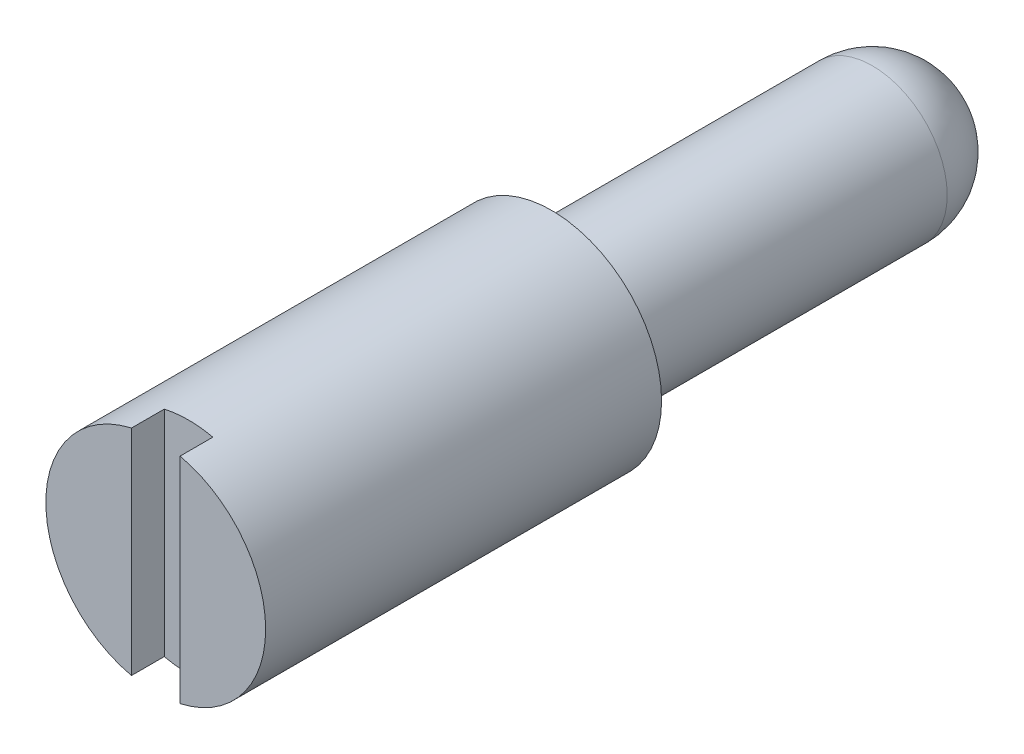
SolidWorks part; units mm, degrees
ref_plane "Front Plane" through (0, 0, 0) normal (0, 0, 1) x (1, 0, 0)
ref_plane "Top Plane" through (0, 0, 0) normal (0, 1, 0) x (1, 0, 0)
ref_plane "Right Plane" through (0, 0, 0) normal (1, 0, 0) x (0, 0, -1)
sketch "Sketch1" plane through (0, 0, 0) normal (0, 1, 0) x (1, 0, 0)
  line L2 (0, 0) -> (2.6454, 0)
  line L3 (2.6454, 0) -> (2.6454, 9.53)
  line L4 (2.6454, 9.53) -> (1.8, 9.53)
  line L5 (1.8, 9.53) -> (1.8, 17.25)
  line L9 (0, 0) -> (0, 19.05)
  arc A0 (1.8, 17.25) -> (0, 19.05) centre (0, 17.25) ccw
  dimension "D3" = 1.8
  dimension "D1" = 19.05
  dimension "D2" = 9.53
revolve "Revolve1" add sketch "Sketch1" angle 360 about L9
cosmetic thread "Cosmetic Thread1"
sketch "Sketch2" plane through (0, 0, 0) normal (0, 1, 0) x (1, 0, 0)
  line L0 (-0.585, 0) -> (-0.585, 0.79)
  line L1 (-2.6454, 0) -> (2.6454, 0) construction
  line L2 (-0.585, 0.79) -> (0.585, 0.79)
  line L3 (0.585, 0.79) -> (0.585, 0)
  line L4 (-0.585, 0) -> (0.585, 0)
  dimension "D1" = 1.17
  dimension "D2" = 0.79
extrude "Cut-Extrude2" cut sketch "Sketch2" against normal through all both and the other way through all
